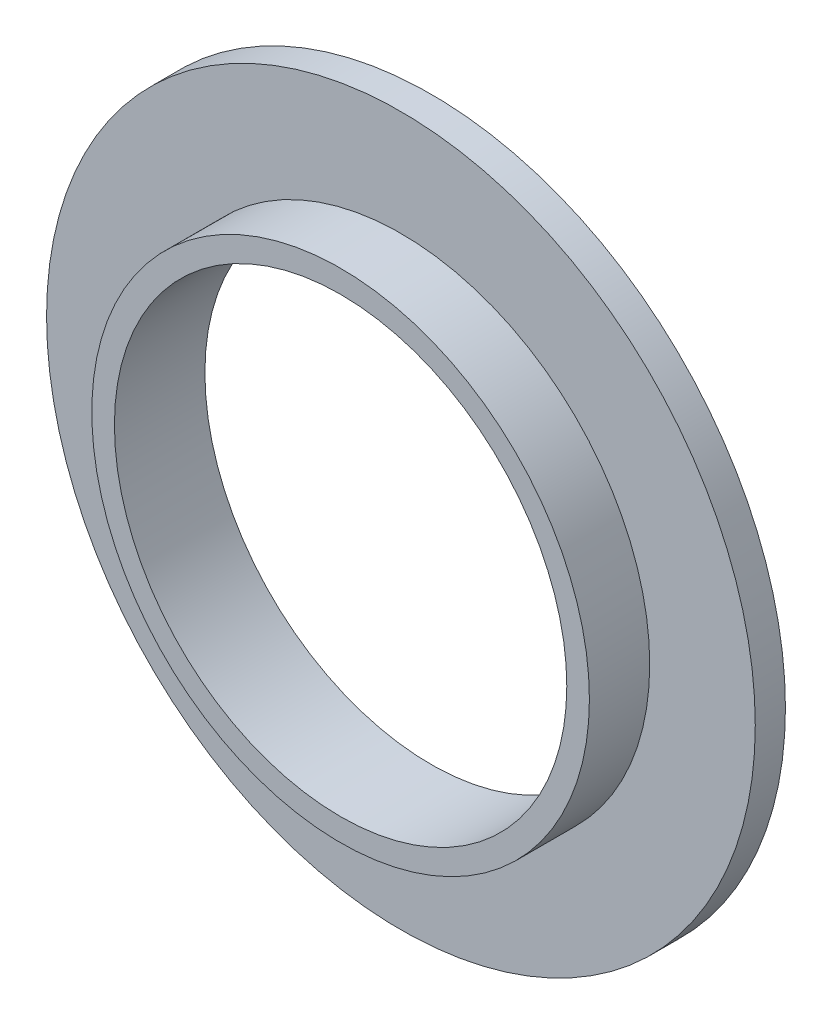
SolidWorks part; units mm, degrees
ref_plane "Front Plane" through (0, 0, 0) normal (0, 0, 1) x (1, 0, 0)
ref_plane "Top Plane" through (0, 0, 0) normal (0, 1, 0) x (1, 0, 0)
ref_plane "Right Plane" through (0, 0, 0) normal (1, 0, 0) x (0, 0, -1)
sketch "Sketch1" plane through (0, 0, 0) normal (0, 0, 1) x (1, 0, 0)
  circle A0 centre (0, 0) radius 23.5
  dimension "D1" = 47
extrude "Boss-Extrude1" add sketch "Sketch1" along normal blind 2
sketch "Sketch2" plane through (0, 0, 2) normal (0, 0, 1) x (1, 0, 0)
  circle A0 centre (0, 0) radius 15
  circle A1 centre (0, 0) radius 16.5
  dimension "D1" = 30
  dimension "D2" = 33
extrude "Boss-Extrude2" add sketch "Sketch2" along normal blind 4
sketch "Sketch3" plane through (0, 0, 0) normal (0, 0, -1) x (-1, 0, 0)
  circle A0 centre (0, 0) radius 15
  dimension "D1" = 30
extrude "Cut-Extrude1" cut sketch "Sketch3" against normal blind 4
